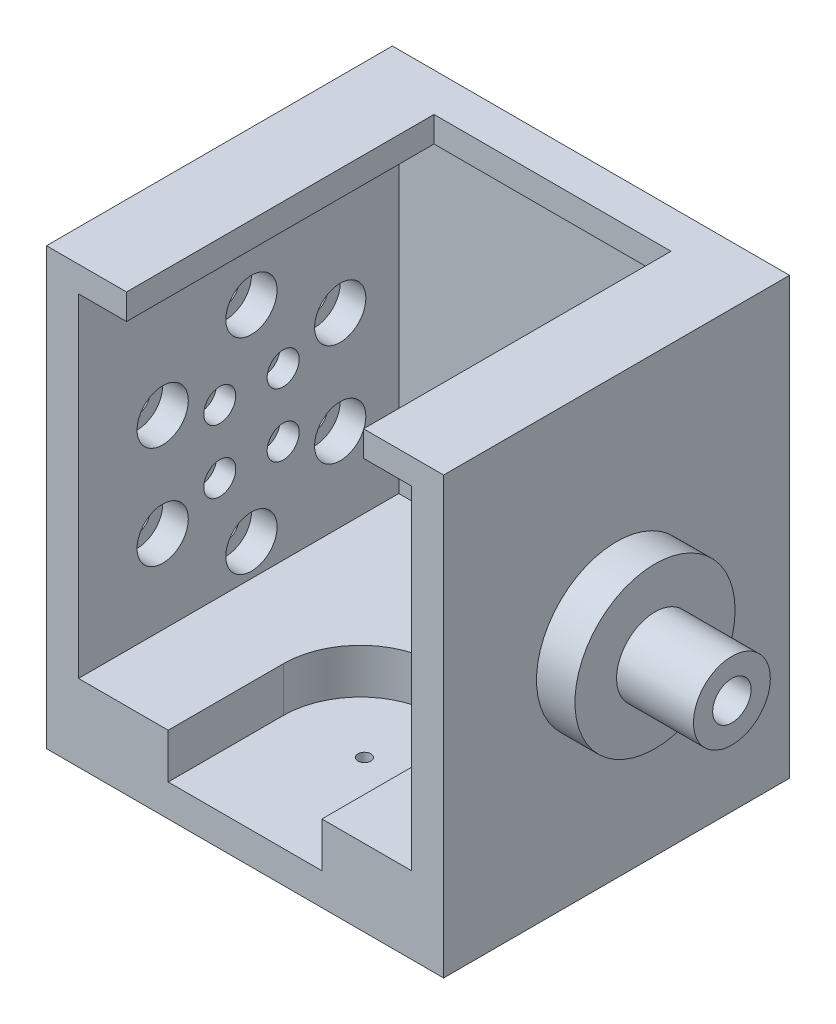
SolidWorks part; units mm, degrees
ref_plane "Front Plane" through (0, 0, 0) normal (0, 0, 1) x (1, 0, 0)
ref_plane "Top Plane" through (0, 0, 0) normal (0, 1, 0) x (1, 0, 0)
ref_plane "Right Plane" through (0, 0, 0) normal (1, 0, 0) x (0, 0, -1)
sketch "Sketch1" plane through (0, 0, 0) normal (0, 1, 0) x (1, 0, 0)
  line L1 (-31, -27) -> (31, -27)
  line L2 (-31, -27) -> (-31, 27)
  line L3 (-31, 27) -> (31, 27)
  line L4 (31, -27) -> (31, 27)
  line L5 (-31, -27) -> (31, 27) construction
  line L6 (-31, 27) -> (31, -27) construction
  point P0 (0, 0)
  dimension "D1" = 54
  dimension "D2" = 62
extrude "Boss-Extrude1" add sketch "Sketch1" along normal blind 12
sketch "Sketch2" plane through (0, 12, 0) normal (0, 1, 0) x (1, 0, 0)
  line L1 (-31, -27) -> (-26, -27)
  line L2 (-31, -27) -> (-31, 22.8513)
  line L4 (-26, -27) -> (-26, 23)
  line L5 (-31, 22.8513) -> (-31, 27)
  line L6 (31, -27) -> (26, -27)
  line L7 (31, -27) -> (31, 22.8513)
  line L9 (26, -27) -> (26, 23)
  line L12 (-26, 23) -> (26, 23)
  line L14 (-31, 27) -> (31, 27)
  line L15 (31, 27) -> (31, 22.8513)
  dimension "D1" = 5
  dimension "D2" = 5
extrude "Boss-Extrude2" add sketch "Sketch2" along normal blind 52
sketch "Sketch3" plane through (0, 64, 0) normal (0, 1, 0) x (1, 0, 0)
  line L5 (-31, -27) -> (31, -27)
  line L6 (-31, -27) -> (-31, 27)
  line L7 (-31, 27) -> (31, 27)
  line L8 (31, -27) -> (31, 27)
extrude "Boss-Extrude3" add sketch "Sketch3" along normal blind 4
sketch "Sketch6" plane through (-31, 0, 0) normal (-1, 0, 0) x (0, 0, 1)
  circle A0 centre (0, 33) radius 20
  dimension "D1" = 40
  dimension "D2" = 33
sketch "Sketch8" plane through (0, 0, -23) normal (0, 0, 1) x (1, 0, 0)
  point P0 (0, 25)
  dimension "D1" = 25
hole_wizard "Ø20.0mm Dowel Hole1" positions "Sketch8" profile "Sketch9" hole size "Ø20.0" standard "ISO" end condition through all
sketch "Sketch9" plane through (0, 25, -23) normal (1, 0, 0) x (0, -1, 0)
  line L0 (0, 0) -> (0, 4)
  line L1 (0, 4) -> (10, 4)
  line L2 (10, 4) -> (10, 0.025)
  line L3 (10, 0.025) -> (10.025, 0)
  line L5 (10.025, 0) -> (0, 0)
  line L6 (-10, 0.025) -> (-10.025, 0) construction
  line L11 (0, -6.35) -> (0, 107.95) construction
  dimension "Thru Hole Dia." = 20
  dimension "Thru Hole Depth" = 4
  dimension "Near C'Sink Dia." = 20.05
  dimension "Near C'Sink Angle" = 90
sketch "Sketch14" plane through (0, 12, 0) normal (0, 1, 0) x (1, 0, 0)
  line L0 (0, -29.3462) -> (0, 6.2162) construction
  line L1 (-12, -9) -> (-12, -27)
  line L2 (-26, -27) -> (26, -27) construction
  line L3 (-12, -27) -> (12, -27)
  line L4 (12, -9) -> (12, -27)
  arc A0 (12, -9) -> (-12, -9) centre (0, -9) ccw
  point P11 (0, -27)
  dimension "D1" = 12
  dimension "D2" = 18
extrude "Cut-Extrude1" cut sketch "Sketch14" against normal blind 7
extrude "Boss-Extrude4" add sketch "Sketch6" along normal blind 6
sketch "Sketch16" plane through (-37, 0, 0) normal (-1, 0, 0) x (0, 0, 1)
  circle A0 centre (0, 49) radius 2
  circle A1 centre (13.8564, 41) radius 2
  circle A2 centre (13.8564, 25) radius 2
  circle A3 centre (0, 17) radius 2
  circle A4 centre (-13.8564, 25) radius 2
  circle A5 centre (-13.8564, 41) radius 2
  point P14 (0, 33)
  point P21 (0, 33)
  dimension "D1" = 4
  dimension "D2" = 6
extrude "Cut-Extrude3" cut sketch "Sketch16" against normal blind 11
sketch "Sketch26" plane through (0, 0, 27) normal (0, 0, 1) x (1, 0, 0)
  line L0 (-26, 64) -> (26, 64) construction
  line L1 (-18.5, 64) -> (18.5, 64)
  line L2 (-18.5, 64) -> (-18.5, 68)
  line L3 (-18.5, 68) -> (18.5, 68)
  line L4 (18.5, 64) -> (18.5, 68)
  line L5 (-31, 68) -> (31, 68) construction
  line L6 (-31, 68) -> (-31, 0) construction
  dimension "D1" = 37
  dimension "D2" = 12.5
extrude "Cut-Extrude10" cut sketch "Sketch26" against normal blind 48
sketch "Sketch29" plane through (0, 5, 0) normal (0, 1, 0) x (1, 0, 0)
  circle A0 centre (0, -8.3673) radius 1
  dimension "D1" = 2
extrude "Cut-Extrude12" cut sketch "Sketch29" against normal blind 48
sketch "Sketch31" plane through (31, 0, 0) normal (1, 0, 0) x (0, 0, -1)
  line L0 (0, 68) -> (0, 33) construction
  line L1 (-27, 68) -> (27, 68) construction
  circle A1 centre (0, 33) radius 12.5
  point P7 (0, 0)
  dimension "D1" = 35
  dimension "D2" = 25
extrude "Boss-Extrude7" add sketch "Sketch31" along normal blind 6
sketch "Sketch33" plane through (37, 0, 0) normal (1, 0, 0) x (0, 0, -1)
  circle A1 centre (0, 33) radius 3
  circle A2 centre (0, 33) radius 6
  dimension "D1" = 6
  dimension "D2" = 12
extrude "Boss-Extrude8" add sketch "Sketch33" along normal blind 12
sketch "Sketch34" plane through (-37, 0, 0) normal (-1, 0, 0) x (0, 0, 1)
  line L0 (0, 33) -> (0, 48) construction
  line L1 (0, 33) -> (-4.9497, 37.9497) construction
  line L2 (0, 33) -> (15, 33) construction
  line L3 (0, 33) -> (0, 18) construction
  line L4 (0, 33) -> (-15, 33) construction
  circle A0 centre (-4.9497, 37.9497) radius 1
  circle A1 centre (4.9497, 37.9497) radius 1
  circle A2 centre (4.9497, 28.0503) radius 1
  circle A3 centre (-4.9497, 28.0503) radius 1
  point P18 (0, 33)
  dimension "D4" = 2
  dimension "D1" = 15
  dimension "D2" = 7
  dimension "D3" = 45
  dimension "D5" = 4
extrude "Cut-Extrude13" cut sketch "Sketch34" against normal blind 11
sketch "Sketch35" plane through (-26, 0, 0) normal (1, 0, 0) x (0, 0, -1)
  line L0 (-4.9497, 37.9497) -> (0, 33) construction
  circle A0 centre (-4.9497, 37.9497) radius 2.5
  circle A1 centre (4.9497, 37.9497) radius 2.5
  circle A2 centre (4.9497, 28.0503) radius 2.5
  circle A3 centre (-4.9497, 28.0503) radius 2.5
  point P13 (0, 33)
  point P26 (0, 33)
  dimension "D1" = 5
  dimension "D2" = 4
extrude "Cut-Extrude15" cut sketch "Sketch35" against normal blind 3
sketch "Sketch37" plane through (-26, 0, 0) normal (1, 0, 0) x (0, 0, -1)
  line L0 (0, 49) -> (0, 33) construction
  circle A0 centre (0, 49) radius 4
  circle A1 centre (13.8564, 41) radius 4
  circle A2 centre (13.8564, 25) radius 4
  circle A3 centre (0, 17) radius 4
  circle A4 centre (-13.8564, 25) radius 4
  circle A5 centre (-13.8564, 41) radius 4
  point P18 (0, 33)
  dimension "D2" = 8
  dimension "D1" = 16
  dimension "D3" = 6
extrude "Cut-Extrude16" cut sketch "Sketch37" against normal blind 4
sketch "Sketch38" plane through (37, 0, 0) normal (1, 0, 0) x (0, 0, -1)
  line L0 (0, 33) -> (0, 35.5) construction
  line L1 (1.6583, 35.5) -> (-1.6583, 35.5)
  arc A1 (1.6583, 35.5) -> (-1.6583, 35.5) centre (0, 33) ccw
  dimension "D2" = 6
  dimension "D1" = 2.5
extrude "Boss-Extrude9" add sketch "Sketch38" along normal blind 10
